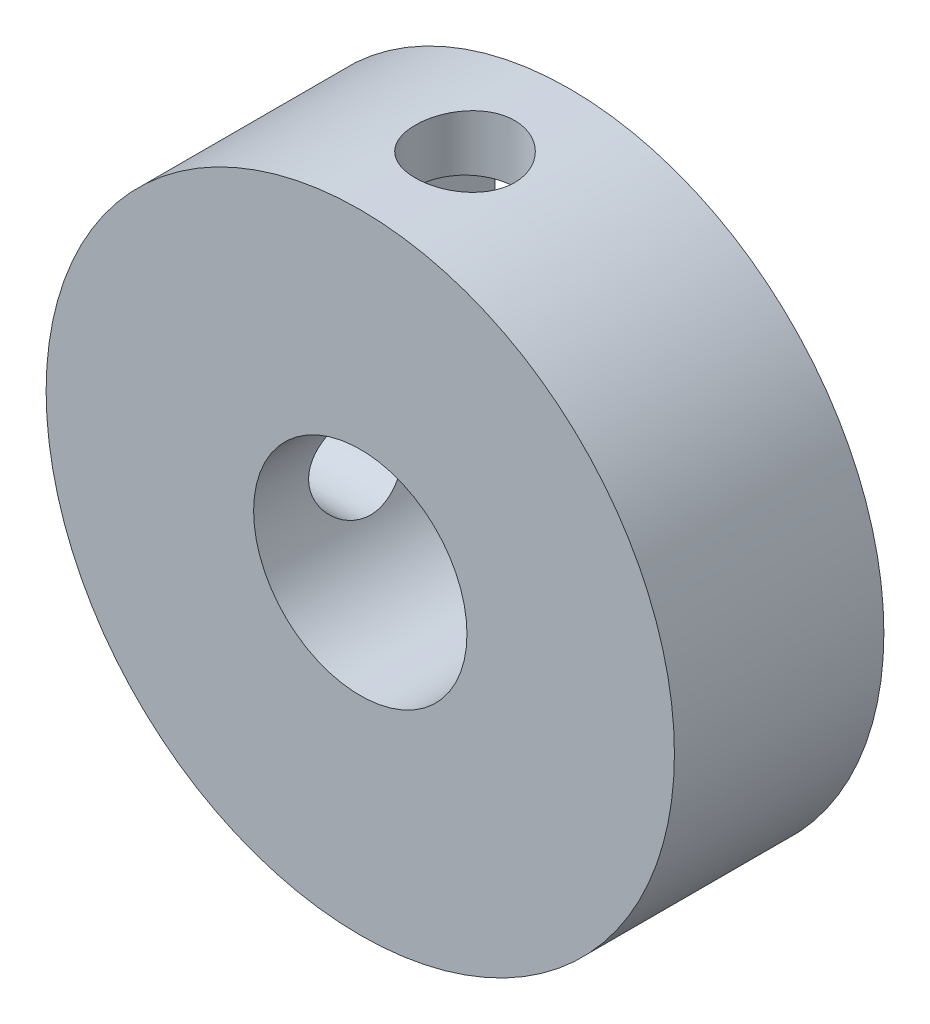
SolidWorks part; units mm, degrees
ref_plane "Front Plane" through (0, 0, 0) normal (0, 0, 1) x (1, 0, 0)
ref_plane "Top Plane" through (0, 0, 0) normal (0, 1, 0) x (1, 0, 0)
ref_plane "Right Plane" through (0, 0, 0) normal (1, 0, 0) x (0, 0, -1)
sketch "Sketch2" plane through (0, 0, 0) normal (0, 0, 1) x (1, 0, 0)
  circle A0 centre (0, 0) radius 12
  circle A1 centre (0, 0) radius 4.075
  dimension "D1" = 8.15
  dimension "D2" = 24
extrude "Boss-Extrude2" add sketch "Sketch2" along normal blind 8
sketch "Sketch5" plane through (0, 0, 0) normal (0, -1, 0) x (0, 0, -1)
  circle A0 centre (-4, 0) radius 1.9
  dimension "D2" = 3.8
  dimension "D1" = 4
extrude "Cut-Extrude8" cut sketch "Sketch5" against normal through all
ref_plane "Plane3" through (0, 7, 0) normal (0, 1, 0) x (1, 0, 0)
sketch "Sketch16" plane through (0, 7, 0) normal (0, 1, 0) x (1, 0, 0)
  line L0 (12, 0) -> (-12, 0) construction
  line L1 (0, -7.2909) -> (2.85, -5.6454)
  line L2 (2.85, -5.6454) -> (2.85, -2.3546)
  line L3 (2.85, -2.3546) -> (0, -0.7091) construction
  line L4 (0, -0.7091) -> (-2.85, -2.3546) construction
  line L5 (-2.85, -2.3546) -> (-2.85, -5.6454)
  line L6 (-2.85, -5.6454) -> (0, -7.2909)
  line L11 (-2.85, -2.3546) -> (2.85, -2.3546) construction
  line L12 (-2.85, -2.3546) -> (-2.85, 0)
  line L13 (-2.85, 0) -> (2.85, 0)
  line L14 (2.85, -2.3546) -> (2.85, 0)
  circle A0 centre (0, -4) radius 2.85 construction
  dimension "D1" = 5.7
  dimension "D2" = 4
extrude "Cut-Extrude7" cut sketch "Sketch16" along normal blind 2.8
pattern_circular "CirPattern1" count 2 every 90 about axis through (0, 0, 0) along (0, 0, 1) of "Cut-Extrude7", "Cut-Extrude8"
sketch "Sketch17" plane through (0, 0, 0) normal (0, 0, -1) x (-1, 0, 0)
  circle A0 centre (0, 0) radius 5.575
  circle A1 centre (0, 0) radius 4.075
  circle A2 centre (0, 0) radius 4.075 construction
  dimension "D1" = 1.5
extrude "Boss-Extrude3" add sketch "Sketch17" along normal blind 2.5
